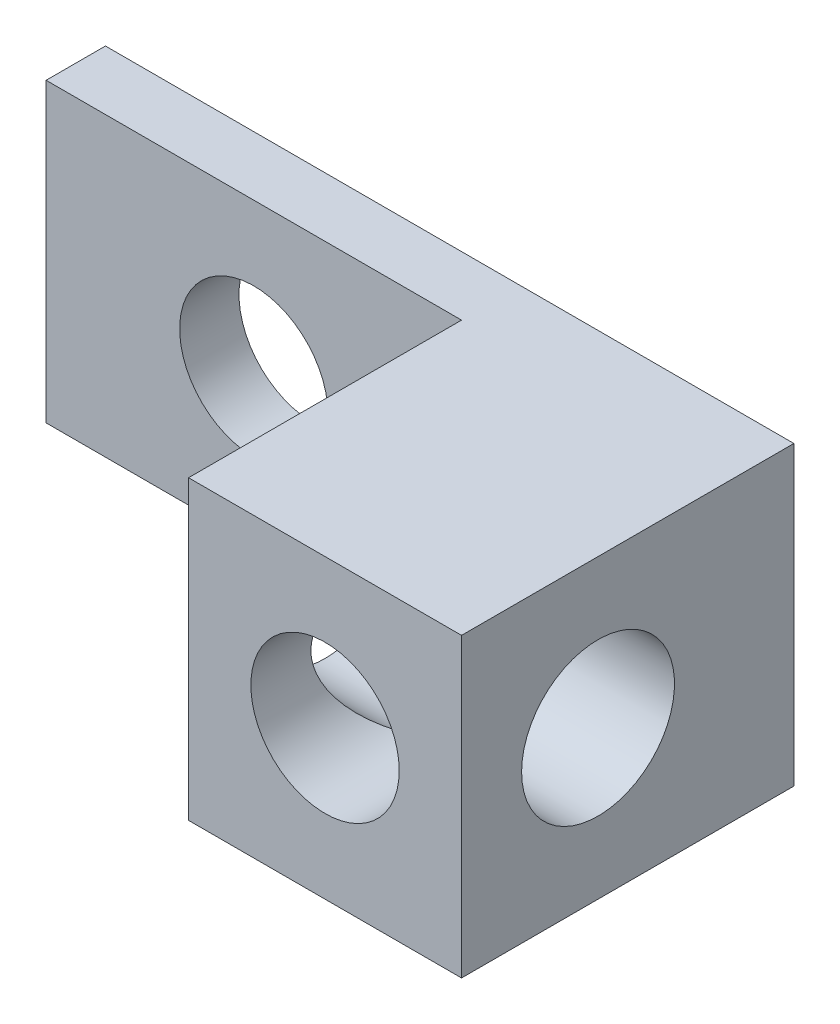
SolidWorks part; units mm, degrees
ref_plane "Front Plane" through (0, 0, 0) normal (0, 0, 1) x (1, 0, 0)
ref_plane "Top Plane" through (0, 0, 0) normal (0, 1, 0) x (1, 0, 0)
ref_plane "Right Plane" through (0, 0, 0) normal (1, 0, 0) x (0, 0, -1)
sketch "Sketch1" plane through (0, 0, 0) normal (0, 1, 0) x (1, 0, 0)
  line L0 (0, 0) -> (0, -14.224)
  line L1 (0, -14.224) -> (-11.684, -14.224)
  line L2 (-11.684, -14.224) -> (-11.684, -2.54)
  line L3 (-11.684, -2.54) -> (-29.464, -2.54)
  line L4 (-29.464, -2.54) -> (-29.464, 0)
  line L5 (-29.464, 0) -> (0, 0)
  dimension "D1" = 29.464
  dimension "D2" = 14.224
  dimension "D3" = 2.54
extrude "Extrude1" add sketch "Sketch1" along normal blind 12.7
sketch "Sketch2" plane through (-11.684, 0, 0) normal (-1, 0, 0) x (0, 0, 1)
  line L0 (8.382, 12.7) -> (8.382, 0) construction
  line L1 (2.54, 12.7) -> (14.224, 12.7) construction
  line L2 (2.54, 0) -> (14.224, 0) construction
  circle A0 centre (8.382, 6.35) radius 3.2715
  dimension "D1" = 6.543
extrude "Extrude2" cut sketch "Sketch2" against normal through all
sketch "Sketch3" plane through (0, 0, 14.224) normal (0, 0, 1) x (1, 0, 0)
  line L0 (-5.842, 12.7) -> (-5.842, 0) construction
  line L1 (-11.684, 12.7) -> (0, 12.7) construction
  line L2 (-11.684, 0) -> (0, 0) construction
  circle A0 centre (-5.842, 6.35) radius 3.175
  dimension "D1" = 6.35
extrude "Extrude3" cut sketch "Sketch3" against normal up to next
sketch "Sketch4" plane through (0, 0, 2.54) normal (0, 0, 1) x (1, 0, 0)
  line L0 (-20.574, 12.7) -> (-20.574, 0) construction
  line L1 (-29.464, 12.7) -> (-11.684, 12.7) construction
  line L2 (-29.464, 0) -> (-11.684, 0) construction
  circle A0 centre (-20.574, 6.35) radius 3.175
  dimension "D1" = 6.35
extrude "Extrude4" cut sketch "Sketch4" against normal through all
